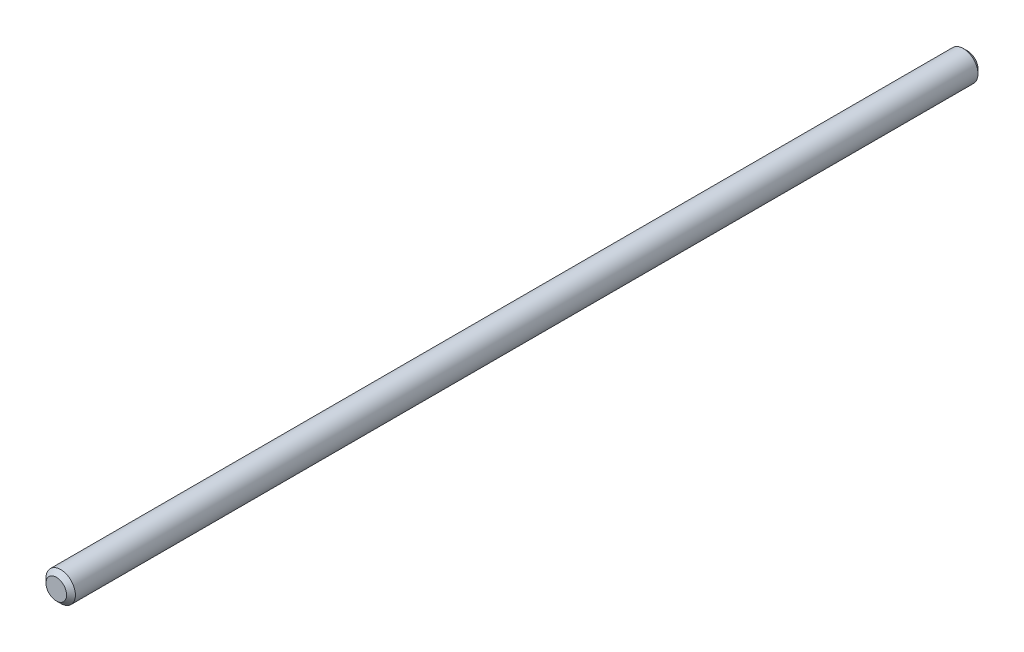
SolidWorks part; units mm, degrees
ref_plane "Front Plane" through (0, 0, 0) normal (0, 0, 1) x (1, 0, 0)
ref_plane "Top Plane" through (0, 0, 0) normal (0, 1, 0) x (1, 0, 0)
ref_plane "Right Plane" through (0, 0, 0) normal (1, 0, 0) x (0, 0, -1)
sketch "Sketch1" plane through (0, 0, 0) normal (0, 0, 1) x (1, 0, 0)
  circle A0 centre (0, 0) radius 2.5
  dimension "D1" = 5
extrude "Boss-Extrude1" add sketch "Sketch1" along normal blind 155
chamfer "Chamfer1" distance 0.75 angle 45 2 edges at (2.5, 0, 0) (2.5, 0, 155)
